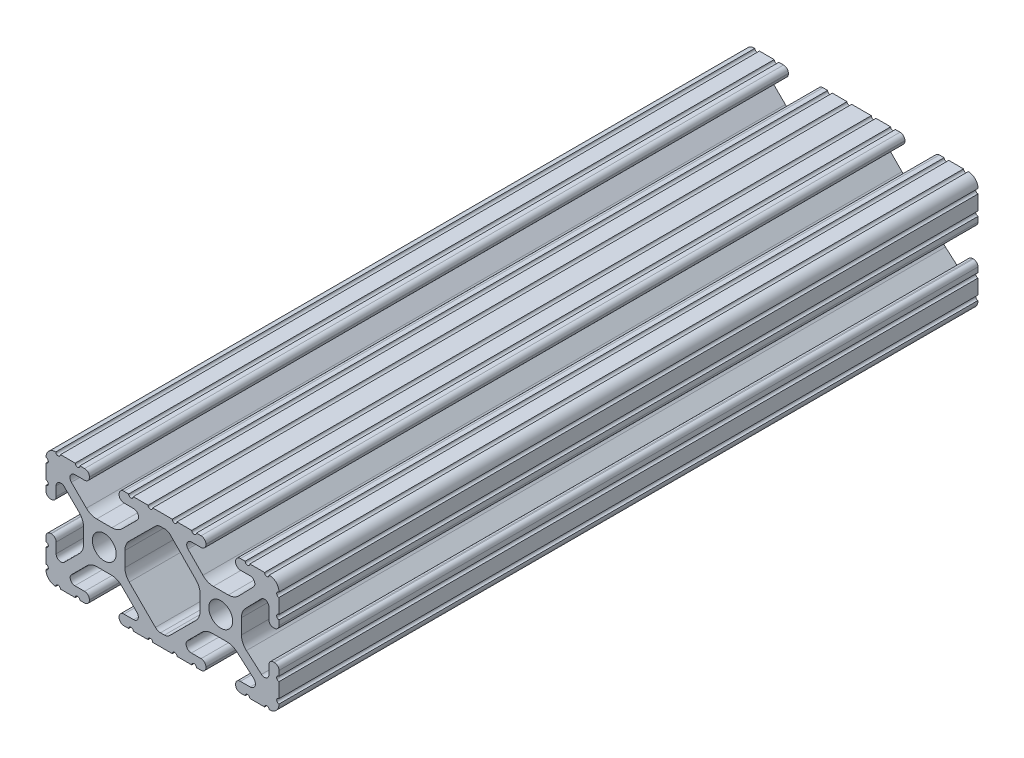
SolidWorks part; units mm, degrees
ref_plane "Front Plane" through (0, 0, 0) normal (0, 0, 1) x (1, 0, 0)
ref_plane "Top Plane" through (0, 0, 0) normal (0, 1, 0) x (1, 0, 0)
ref_plane "Right Plane" through (0, 0, 0) normal (1, 0, 0) x (0, 0, -1)
sketch "Sketch1" plane through (0, 0, 0) normal (0, 0, 1) x (1, 0, 0)
  line L0 (-7.2595, -3.8694) -> (-1.5457, -9.5728)
  line L1 (-8.1915, 1.6223) -> (-8.1915, -1.6223)
  line L2 (-1.504, 9.5765) -> (-7.252, 3.8768)
  line L3 (0.5515, 10.033) -> (-0.3952, 10.033)
  line L4 (7.2829, 3.8459) -> (1.6756, 9.5611)
  line L5 (8.1915, -1.6223) -> (8.1915, 1.6223)
  line L6 (1.5457, -9.5728) -> (7.2595, -3.8694)
  line L7 (-0.4332, -10.033) -> (0.4332, -10.033)
  line L8 (18.0171, 12.7) -> (16.9875, 12.7)
  line L9 (15.9385, 11.651) -> (15.9385, 11.5392)
  line L10 (16.9875, 10.4902) -> (19.1164, 10.4902)
  line L11 (19.8441, 8.7652) -> (16.619, 5.4551)
  line L12 (14.3449, 4.4958) -> (11.0833, 4.4958)
  line L13 (8.817, 5.4472) -> (5.5642, 8.7627)
  line L14 (6.2894, 10.4902) -> (8.4125, 10.4902)
  line L15 (9.4615, 11.5392) -> (9.4615, 11.651)
  line L16 (8.4125, 12.7) -> (7.3829, 12.7)
  line L17 (6.3669, 12.7) -> (3.1496, 12.7)
  line L18 (2.1336, 12.7) -> (-2.1336, 12.7)
  line L19 (-3.1496, 12.7) -> (-6.3669, 12.7)
  line L20 (-7.3829, 12.7) -> (-8.4125, 12.7)
  line L21 (-9.4615, 11.651) -> (-9.4615, 11.5392)
  line L22 (-8.4125, 10.4902) -> (-6.2836, 10.4902)
  line L23 (-5.5326, 8.6661) -> (-8.81, 5.4163)
  line L24 (-11.0455, 4.4958) -> (-14.3545, 4.4958)
  line L25 (-16.59, 5.4163) -> (-19.8674, 8.6661)
  line L26 (-19.1164, 10.4902) -> (-16.9875, 10.4902)
  line L27 (-15.9385, 11.5392) -> (-15.9385, 11.651)
  line L28 (-16.9875, 12.7) -> (-18.0171, 12.7)
  line L29 (-19.0331, 12.7) -> (-22.2504, 12.7)
  line L30 (-25.4, 9.5504) -> (-25.4, 6.3331)
  line L31 (-25.4, 5.3171) -> (-25.4, 4.2375)
  line L32 (-24.401, 3.2385) -> (-24.2392, 3.2385)
  line L33 (-23.1902, 4.2875) -> (-23.1902, 6.3347)
  line L34 (-21.434, 7.0665) -> (-18.148, 3.8082)
  line L35 (-17.2085, 1.5536) -> (-17.2085, -1.6952)
  line L36 (-18.1405, -3.9423) -> (-21.4316, -7.2274)
  line L37 (-23.1902, -6.498) -> (-23.1902, -4.2875)
  line L38 (-24.2392, -3.2385) -> (-24.351, -3.2385)
  line L39 (-25.4, -4.2875) -> (-25.4, -5.3171)
  line L40 (-25.4, -6.3331) -> (-25.4, -9.5504)
  line L41 (-22.2504, -12.7) -> (-19.0331, -12.7)
  line L42 (-18.0171, -12.7) -> (-16.9875, -12.7)
  line L43 (-15.9384, -11.651) -> (-15.9384, -11.5392)
  line L44 (-16.9875, -10.4902) -> (-19.1164, -10.4902)
  line L45 (-19.8341, -8.7551) -> (-16.4966, -5.4237)
  line L46 (-14.2536, -4.4958) -> (-11.1464, -4.4958)
  line L47 (-8.9034, -5.4237) -> (-5.5659, -8.7551)
  line L48 (-6.2836, -10.4902) -> (-8.4125, -10.4902)
  line L49 (-9.4616, -11.5392) -> (-9.4616, -11.651)
  line L50 (-8.4125, -12.7) -> (-7.3829, -12.7)
  line L51 (-6.3669, -12.7) -> (-3.1496, -12.7)
  line L52 (-2.1336, -12.7) -> (2.1336, -12.7)
  line L53 (3.1496, -12.7) -> (6.3669, -12.7)
  line L54 (7.3829, -12.7) -> (8.4125, -12.7)
  line L55 (9.4616, -11.651) -> (9.4616, -11.5392)
  line L56 (8.4125, -10.4902) -> (6.2894, -10.4902)
  line L57 (5.4807, -8.5353) -> (8.5979, -5.4237)
  line L58 (10.8409, -4.4958) -> (14.1026, -4.4958)
  line L59 (16.1879, -5.2766) -> (19.8682, -8.4822)
  line L60 (19.1164, -10.4902) -> (16.9875, -10.4902)
  line L61 (15.9384, -11.5392) -> (15.9384, -11.651)
  line L62 (16.9875, -12.7) -> (18.0171, -12.7)
  line L63 (19.0331, -12.7) -> (22.2504, -12.7)
  line L64 (25.4, -9.5504) -> (25.4, -6.3331)
  line L65 (25.4, -5.3171) -> (25.4, -4.2375)
  line L66 (24.401, -3.2385) -> (24.1892, -3.2385)
  line L67 (23.1902, -4.2375) -> (23.1902, -6.1559)
  line L68 (21.584, -6.8869) -> (18.2982, -4.025)
  line L69 (17.2085, -1.6308) -> (17.2085, 1.6308)
  line L70 (18.1094, 3.8465) -> (21.5263, 7.3534)
  line L71 (23.1902, 6.6769) -> (23.1902, 4.2375)
  line L72 (24.1892, 3.2385) -> (24.401, 3.2385)
  line L73 (25.4, 4.2375) -> (25.4, 5.3171)
  line L74 (25.4, 6.3332) -> (25.4, 9.5504)
  line L75 (22.2504, 12.7) -> (19.0331, 12.7)
  circle A0 centre (-12.7, 0) radius 2.6035
  circle A1 centre (12.7, 0) radius 2.6035
  arc A2 (-1.5457, -9.5728) -> (-0.4332, -10.033) centre (-0.4332, -8.4582) ccw
  arc A3 (-8.1915, -1.6223) -> (-7.2595, -3.8694) centre (-5.0165, -1.6223) ccw
  arc A4 (-7.252, 3.8768) -> (-8.1915, 1.6223) centre (-5.0165, 1.6223) ccw
  arc A5 (-0.3952, 10.033) -> (-1.504, 9.5765) centre (-0.3952, 8.4582) ccw
  arc A6 (1.6756, 9.5611) -> (0.5515, 10.033) centre (0.5515, 8.4582) ccw
  arc A7 (8.1915, 1.6223) -> (7.2829, 3.8459) centre (5.0165, 1.6223) ccw
  arc A8 (7.2595, -3.8694) -> (8.1915, -1.6223) centre (5.0165, -1.6223) ccw
  arc A9 (0.4332, -10.033) -> (1.5457, -9.5728) centre (0.4332, -8.4582) ccw
  arc A10 (18.0171, 12.7) -> (19.0331, 12.7) centre (18.5251, 12.7) ccw
  arc A11 (16.9875, 12.7) -> (15.9385, 11.651) centre (16.9875, 11.651) ccw
  arc A12 (15.9385, 11.5392) -> (16.9875, 10.4902) centre (16.9875, 11.5392) ccw
  arc A13 (19.8441, 8.7652) -> (19.1164, 10.4902) centre (19.1164, 9.4742) ccw
  arc A14 (14.3449, 4.4958) -> (16.619, 5.4551) centre (14.3449, 7.6708) ccw
  arc A15 (8.817, 5.4472) -> (11.0833, 4.4958) centre (11.0833, 7.6708) ccw
  arc A16 (6.2894, 10.4902) -> (5.5642, 8.7627) centre (6.2894, 9.4742) ccw
  arc A17 (8.4125, 10.4902) -> (9.4615, 11.5392) centre (8.4125, 11.5392) ccw
  arc A18 (9.4615, 11.651) -> (8.4125, 12.7) centre (8.4125, 11.651) ccw
  arc A19 (6.3669, 12.7) -> (7.3829, 12.7) centre (6.8749, 12.7) ccw
  arc A20 (2.1336, 12.7) -> (3.1496, 12.7) centre (2.6416, 12.7) ccw
  arc A21 (-3.1496, 12.7) -> (-2.1336, 12.7) centre (-2.6416, 12.7) ccw
  arc A22 (-7.3829, 12.7) -> (-6.3669, 12.7) centre (-6.8749, 12.7) ccw
  arc A23 (-8.4125, 12.7) -> (-9.4615, 11.651) centre (-8.4125, 11.651) ccw
  arc A24 (-9.4615, 11.5392) -> (-8.4125, 10.4902) centre (-8.4125, 11.5392) ccw
  arc A25 (-5.5326, 8.6661) -> (-6.2836, 10.4902) centre (-6.2836, 9.4235) ccw
  arc A26 (-11.0455, 4.4958) -> (-8.81, 5.4163) centre (-11.0455, 7.6708) ccw
  arc A27 (-16.59, 5.4163) -> (-14.3545, 4.4958) centre (-14.3545, 7.6708) ccw
  arc A28 (-19.1164, 10.4902) -> (-19.8674, 8.6661) centre (-19.1164, 9.4235) ccw
  arc A29 (-16.9875, 10.4902) -> (-15.9385, 11.5392) centre (-16.9875, 11.5392) ccw
  arc A30 (-15.9385, 11.651) -> (-16.9875, 12.7) centre (-16.9875, 11.651) ccw
  arc A31 (-19.0331, 12.7) -> (-18.0171, 12.7) centre (-18.5251, 12.7) ccw
  arc A32 (-23.2664, 12.6998) -> (-22.2504, 12.7) centre (-22.7584, 12.7) ccw
  arc A33 (-23.2664, 12.6998) -> (-25.3998, 10.5664) centre (-23.2918, 10.5918) ccw
  arc A34 (-25.4, 9.5504) -> (-25.3998, 10.5664) centre (-25.4, 10.0584) ccw
  arc A35 (-25.4, 5.3171) -> (-25.4, 6.3331) centre (-25.4, 5.8251) ccw
  arc A36 (-25.4, 4.2375) -> (-24.401, 3.2385) centre (-24.401, 4.2375) ccw
  arc A37 (-24.2392, 3.2385) -> (-23.1902, 4.2875) centre (-24.2392, 4.2875) ccw
  arc A38 (-21.434, 7.0665) -> (-23.1902, 6.3347) centre (-22.1596, 6.3347) ccw
  arc A39 (-17.2085, 1.5536) -> (-18.148, 3.8082) centre (-20.3835, 1.5536) ccw
  arc A40 (-18.1405, -3.9423) -> (-17.2085, -1.6952) centre (-20.3835, -1.6952) ccw
  arc A41 (-23.1902, -6.498) -> (-21.4316, -7.2274) centre (-22.1596, -6.498) ccw
  arc A42 (-23.1902, -4.2875) -> (-24.2392, -3.2385) centre (-24.2392, -4.2875) ccw
  arc A43 (-24.351, -3.2385) -> (-25.4, -4.2875) centre (-24.351, -4.2875) ccw
  arc A44 (-25.4, -6.3331) -> (-25.4, -5.3171) centre (-25.4, -5.8251) ccw
  arc A45 (-25.3998, -10.5664) -> (-25.4, -9.5504) centre (-25.4, -10.0584) ccw
  arc A46 (-25.3998, -10.5664) -> (-23.2664, -12.6998) centre (-23.2918, -10.5918) ccw
  arc A47 (-22.2504, -12.7) -> (-23.2664, -12.6998) centre (-22.7584, -12.7) ccw
  arc A48 (-18.0171, -12.7) -> (-19.0331, -12.7) centre (-18.5251, -12.7) ccw
  arc A49 (-16.9875, -12.7) -> (-15.9384, -11.651) centre (-16.9875, -11.651) ccw
  arc A50 (-15.9384, -11.5392) -> (-16.9875, -10.4902) centre (-16.9875, -11.5392) ccw
  arc A51 (-19.8341, -8.7551) -> (-19.1164, -10.4902) centre (-19.1164, -9.4742) ccw
  arc A52 (-14.2536, -4.4958) -> (-16.4966, -5.4237) centre (-14.2536, -7.6708) ccw
  arc A53 (-8.9034, -5.4237) -> (-11.1464, -4.4958) centre (-11.1464, -7.6708) ccw
  arc A54 (-6.2836, -10.4902) -> (-5.5659, -8.7551) centre (-6.2836, -9.4742) ccw
  arc A55 (-8.4125, -10.4902) -> (-9.4616, -11.5392) centre (-8.4125, -11.5392) ccw
  arc A56 (-9.4616, -11.651) -> (-8.4125, -12.7) centre (-8.4125, -11.651) ccw
  arc A57 (-6.3669, -12.7) -> (-7.3829, -12.7) centre (-6.8749, -12.7) ccw
  arc A58 (-2.1336, -12.7) -> (-3.1496, -12.7) centre (-2.6416, -12.7) ccw
  arc A59 (3.1496, -12.7) -> (2.1336, -12.7) centre (2.6416, -12.7) ccw
  arc A60 (7.3829, -12.7) -> (6.3669, -12.7) centre (6.8749, -12.7) ccw
  arc A61 (8.4125, -12.7) -> (9.4616, -11.651) centre (8.4125, -11.651) ccw
  arc A62 (9.4616, -11.5392) -> (8.4125, -10.4902) centre (8.4125, -11.5392) ccw
  arc A63 (5.4807, -8.5353) -> (6.2894, -10.4902) centre (6.2894, -9.3455) ccw
  arc A64 (10.8409, -4.4958) -> (8.5979, -5.4237) centre (10.8409, -7.6708) ccw
  arc A65 (16.1879, -5.2766) -> (14.1026, -4.4958) centre (14.1026, -7.6708) ccw
  arc A66 (19.1164, -10.4902) -> (19.8682, -8.4822) centre (19.1164, -9.3455) ccw
  arc A67 (16.9875, -10.4902) -> (15.9384, -11.5392) centre (16.9875, -11.5392) ccw
  arc A68 (15.9384, -11.651) -> (16.9875, -12.7) centre (16.9875, -11.651) ccw
  arc A69 (19.0331, -12.7) -> (18.0171, -12.7) centre (18.5251, -12.7) ccw
  arc A70 (23.2664, -12.6998) -> (22.2504, -12.7) centre (22.7584, -12.7) ccw
  arc A71 (23.2664, -12.6998) -> (25.3998, -10.5664) centre (23.2918, -10.5918) ccw
  arc A72 (25.4, -9.5504) -> (25.3998, -10.5664) centre (25.4, -10.0584) ccw
  arc A73 (25.4, -5.3171) -> (25.4, -6.3331) centre (25.4, -5.8251) ccw
  arc A74 (25.4, -4.2375) -> (24.401, -3.2385) centre (24.401, -4.2375) ccw
  arc A75 (24.1892, -3.2385) -> (23.1902, -4.2375) centre (24.1892, -4.2375) ccw
  arc A76 (21.584, -6.8869) -> (23.1902, -6.1559) centre (22.2207, -6.1559) ccw
  arc A77 (17.2085, -1.6308) -> (18.2982, -4.025) centre (20.3835, -1.6308) ccw
  arc A78 (18.1094, 3.8465) -> (17.2085, 1.6308) centre (20.3835, 1.6308) ccw
  arc A79 (23.1902, 6.6769) -> (21.5263, 7.3534) centre (22.2207, 6.6769) ccw
  arc A80 (23.1902, 4.2375) -> (24.1892, 3.2385) centre (24.1892, 4.2375) ccw
  arc A81 (24.401, 3.2385) -> (25.4, 4.2375) centre (24.401, 4.2375) ccw
  arc A82 (25.4, 6.3332) -> (25.4, 5.3171) centre (25.4, 5.8251) ccw
  arc A83 (25.3998, 10.5664) -> (25.4, 9.5504) centre (25.4, 10.0584) ccw
  arc A84 (25.3998, 10.5664) -> (23.2664, 12.6998) centre (23.2918, 10.5918) ccw
  arc A85 (22.2504, 12.7) -> (23.2664, 12.6998) centre (22.7584, 12.7) ccw
  point P248 (0, 10.033)
extrude "Boss-Extrude1" add sketch "Sketch1" along normal mid plane 152.4
